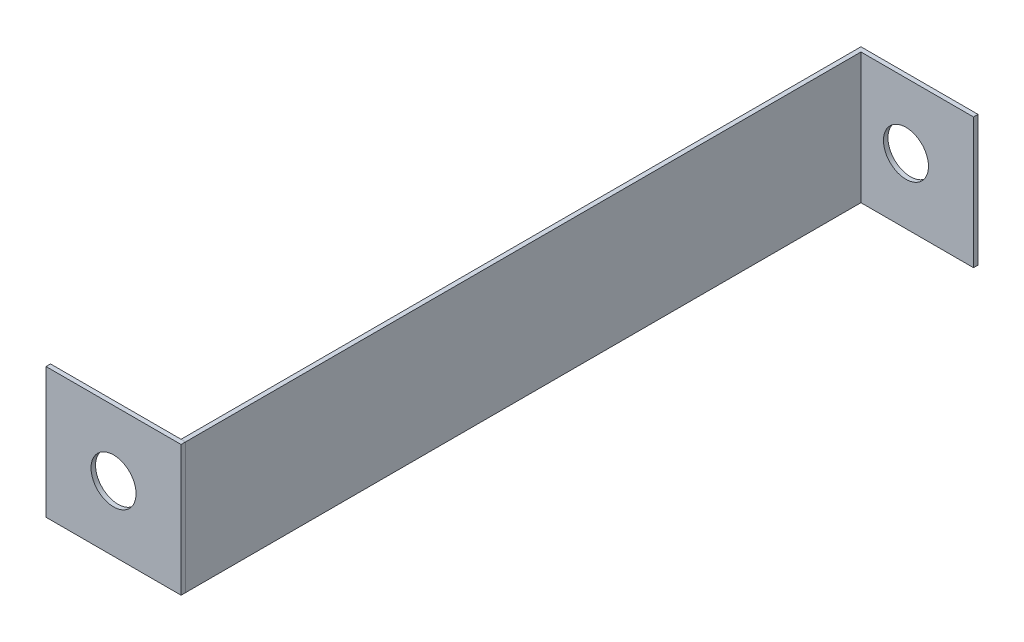
SolidWorks part; units mm, degrees
ref_plane "Płaszczyzna przednia" through (0, 0, 0) normal (0, 0, 1) x (1, 0, 0)
ref_plane "Płaszczyzna górna" through (0, 0, 0) normal (0, 1, 0) x (1, 0, 0)
ref_plane "Płaszczyzna prawa" through (0, 0, 0) normal (1, 0, 0) x (0, 0, -1)
sketch "Szkic1" plane through (0, 0, 0) normal (0, 0, 1) x (1, 0, 0)
  line L0 (0, 0) -> (0, 29)
  line L1 (0, 29) -> (-26, 29)
  line L2 (-26, 29) -> (-26, 0)
  line L3 (-26, 0) -> (0, 0)
  circle A0 centre (-15, 14.5) radius 5
  dimension "D3" = 10
  dimension "D1" = 29
  dimension "D2" = 26
  dimension "D4" = 15
extrude "Dodanie-wyciągnięcie1" add sketch "Szkic1" along normal blind 1
sketch "Szkic2" plane through (0, 0, 1) normal (0, 0, 1) x (1, 0, 0)
  line L0 (-26, 0) -> (-25, 0)
  line L1 (-26, 0) -> (0, 0) construction
  line L2 (-25, 0) -> (-25, 29)
  line L3 (0, 29) -> (-26, 29) construction
  line L4 (-25, 29) -> (-26, 29)
  line L5 (-26, 29) -> (-26, 0)
  dimension "D1" = 1
extrude "Dodanie-wyciągnięcie2" add sketch "Szkic2" along normal blind 150
sketch "Szkic3" plane through (0, 0, 151) normal (0, 0, 1) x (1, 0, 0)
  line L0 (-25, 0) -> (-55, 0)
  line L1 (-25, 29) -> (-55, 29)
  line L2 (-55, 29) -> (-55, 0)
  circle A0 centre (-40, 14.5) radius 5
  line M1 (-26, 29) -> (-26, 0)
  line M2 (-26, 0) -> (-25, 0)
  line M3 (-25, 0) -> (-25, 29)
  line M4 (-25, 29) -> (-26, 29)
  dimension "D2" = 10
  dimension "D1" = 30
extrude "Dodanie-wyciągnięcie3" add sketch "Szkic3" along normal blind 1 separate body contours L1 L2 L0 A0 M1 | M4 M1 M2 M3
